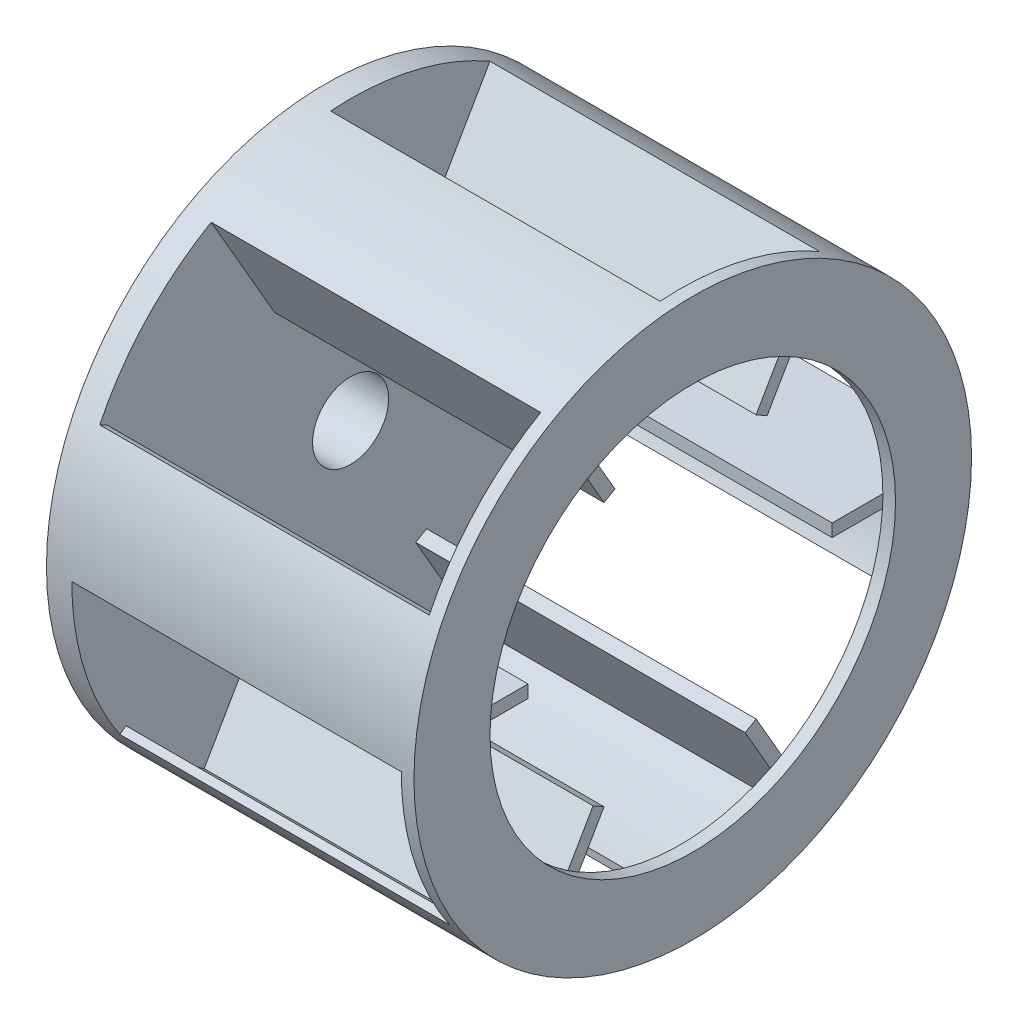
SolidWorks part; units mm, degrees
ref_plane "Front Plane" through (0, 0, 0) normal (0, 0, 1) x (1, 0, 0)
ref_plane "Top Plane" through (0, 0, 0) normal (0, 1, 0) x (1, 0, 0)
ref_plane "Right Plane" through (0, 0, 0) normal (1, 0, 0) x (0, 0, -1)
sketch "Sketch5" plane through (0, 0, 0) normal (1, 0, 0) x (0, 0, -1)
  circle A0 centre (0, 0) radius 139.7
  dimension "D1" = 279.4
extrude "Boss-Extrude3" add sketch "Sketch5" along normal blind 12.7
sketch "Sketch6" plane through (0, 0, 0) normal (-1, 0, 0) x (0, 0, 1)
  circle A0 centre (0, 0) radius 38.1
  circle A1 centre (0, 0) radius 19.05
  dimension "D1" = 76.2
  dimension "D2" = 38.1
extrude "Boss-Extrude4" add sketch "Sketch6" along normal blind 63.5
sketch "Sketch7" plane through (0, 0, 0) normal (-1, 0, 0) x (0, 0, 1)
  circle A0 centre (0, 0) radius 19.05
extrude "Cut-Extrude3" cut sketch "Sketch7" against normal blind 63.5
sketch "Sketch9" plane through (12.7, 0, 0) normal (1, 0, 0) x (0, 0, -1)
  line L0 (-139.7, 0) -> (-76.2, 0)
  line L1 (-76.2, 0) -> (-76.2, 6.35)
  line L2 (-76.2, 6.35) -> (-135.7416, 6.35)
  line L3 (-125.6979, 60.96) -> (-122.2698, 59.2975)
  line L4 (-115.6419, -78.3776) -> (-112.488, -76.24)
  line L5 (-43.5993, -62.8161) -> (-73.37, -114.3806)
  line L6 (-38.1, -65.9911) -> (-43.5993, -62.8161)
  line L7 (-69.85, -120.9837) -> (-38.1, -65.9911)
  line L8 (10.0561, -139.3376) -> (9.7818, -135.5375)
  line L9 (32.6007, -69.1661) -> (62.3715, -120.7306)
  line L10 (38.1, -65.9911) -> (32.6007, -69.1661)
  line L11 (69.85, -120.9837) -> (38.1, -65.9911)
  line L12 (125.6979, -60.96) -> (122.2698, -59.2975)
  line L13 (76.2, -6.35) -> (135.7416, -6.35)
  line L14 (76.2, 0) -> (76.2, -6.35)
  line L15 (139.7, 0) -> (76.2, 0)
  line L16 (115.6419, 78.3776) -> (112.488, 76.24)
  line L17 (43.5993, 62.8161) -> (73.37, 114.3806)
  line L18 (38.1, 65.9911) -> (43.5993, 62.8161)
  line L19 (69.85, 120.9837) -> (38.1, 65.9911)
  line L20 (-10.0561, 139.3376) -> (-9.7818, 135.5375)
  line L21 (-32.6007, 69.1661) -> (-62.3715, 120.7306)
  line L22 (-38.1, 65.9911) -> (-32.6007, 69.1661)
  line L23 (-69.85, 120.9837) -> (-38.1, 65.9911)
  circle A0 centre (0, 0) radius 139.7 construction
  arc A1 (-125.6979, 60.96) -> (-139.7, 0) centre (0, 0) ccw
  arc A2 (-122.2698, 59.2975) -> (-135.7416, 6.35) centre (0, 0) ccw
  circle A3 centre (0, 0) radius 135.89 construction
  circle A4 centre (0, 0) radius 139.7 construction
  arc A5 (-112.488, -76.24) -> (-73.37, -114.3806) centre (0, 0) ccw
  arc A6 (-115.6419, -78.3776) -> (-69.85, -120.9837) centre (0, 0) ccw
  arc A7 (9.7818, -135.5375) -> (62.3715, -120.7306) centre (0, 0) ccw
  arc A8 (10.0561, -139.3376) -> (69.85, -120.9837) centre (0, 0) ccw
  arc A9 (122.2698, -59.2975) -> (135.7416, -6.35) centre (0, 0) ccw
  arc A10 (125.6979, -60.96) -> (139.7, 0) centre (0, 0) ccw
  arc A11 (112.488, 76.24) -> (73.37, 114.3806) centre (0, 0) ccw
  arc A12 (115.6419, 78.3776) -> (69.85, 120.9837) centre (0, 0) ccw
  arc A13 (-9.7818, 135.5375) -> (-62.3715, 120.7306) centre (0, 0) ccw
  arc A14 (-10.0561, 139.3376) -> (-69.85, 120.9837) centre (0, 0) ccw
  dimension "D1" = 3.81
  dimension "D4" = 60.96
  dimension "D2" = 63.5
  dimension "D3" = 6.35
  dimension "D5" = 6
extrude "Boss-Extrude5" add sketch "Sketch9" along normal blind 165.1
ref_plane "Plane2" through (177.8, 0, 0) normal (1, 0, 0) x (0, 0, -1)
sketch "Sketch10" plane through (177.8, 0, 0) normal (1, 0, 0) x (0, 0, -1)
  circle A0 centre (0, 0) radius 139.7
extrude "Boss-Extrude6" add sketch "Sketch10" along normal blind 6.35
sketch "Sketch11" plane through (184.15, 0, 0) normal (1, 0, 0) x (0, 0, -1)
  circle A0 centre (0, 0) radius 101.6
  dimension "D1" = 203.2
extrude "Cut-Extrude4" cut sketch "Sketch11" against normal blind 6.35
